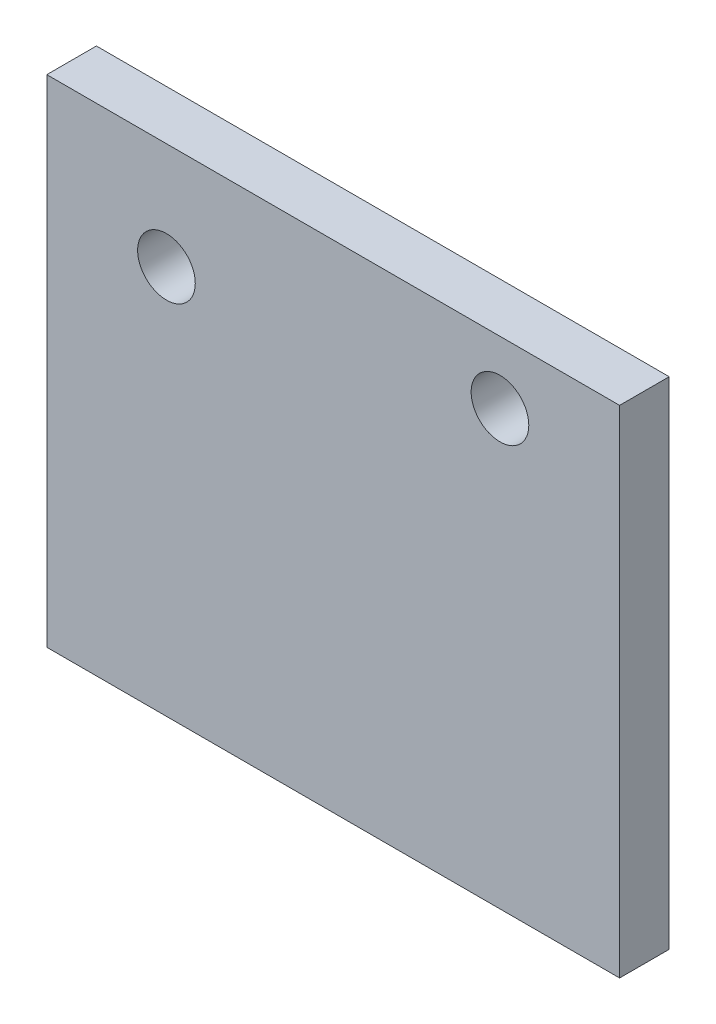
SolidWorks part; units mm, degrees
ref_plane "Płaszczyzna przednia" through (0, 0, 0) normal (0, 0, 1) x (1, 0, 0)
ref_plane "Płaszczyzna górna" through (0, 0, 0) normal (0, 1, 0) x (1, 0, 0)
ref_plane "Płaszczyzna prawa" through (0, 0, 0) normal (1, 0, 0) x (0, 0, -1)
sketch "Szkic2" plane through (0, 0, 0) normal (0, 0, 1) x (1, 0, 0)
  line L0 (96.5, -86) -> (96.5, -400)
  line L1 (0, 0) -> (462, 0)
  line L2 (0, 0) -> (0, -400)
  line L3 (0, -400) -> (462, -400)
  line L4 (462, 0) -> (462, -400)
  line L5 (365.5, -50.5) -> (365.5, -400)
  circle A0 centre (96.5, -86) radius 23.25
  circle A1 centre (365.5, -50.5) radius 23.25
  dimension "D3" = 46.5
  dimension "D5" = 46.5
  dimension "D1" = 400
  dimension "D2" = 462
  dimension "D4" = 314
  dimension "D6" = 349.5
  dimension "D7" = 96.5
  dimension "D8" = 269
extrude "Dodanie-wyciągnięcie1" add sketch "Szkic2" along normal blind 40
